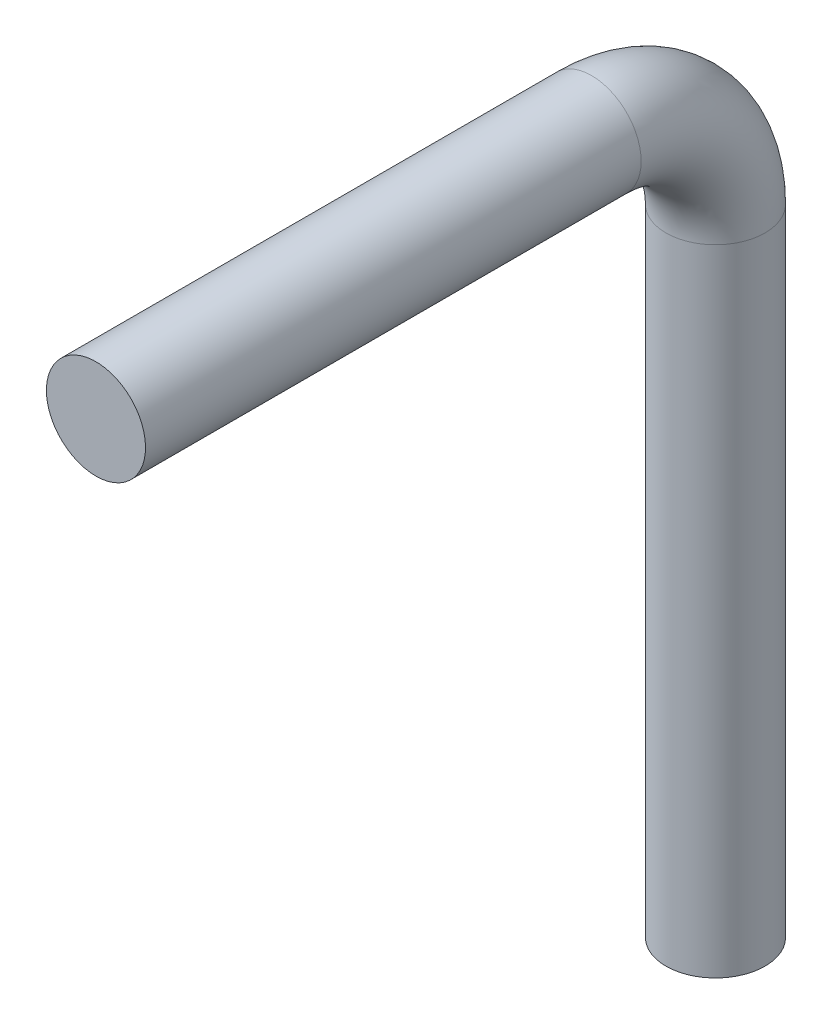
SolidWorks part; units mm, degrees
ref_plane "Front Plane" through (0, 0, 0) normal (0, 0, 1) x (1, 0, 0)
ref_plane "Top Plane" through (0, 0, 0) normal (0, 1, 0) x (1, 0, 0)
ref_plane "Right Plane" through (0, 0, 0) normal (1, 0, 0) x (0, 0, -1)
sketch "Sketch1" plane through (0, 0, 0) normal (0, 1, 0) x (1, 0, 0)
  circle A0 centre (0, 0) radius 5.08
  dimension "D1" = 10.16
sketch "Sketch2" plane through (0, 0, 0) normal (1, 0, 0) x (0, 0, -1)
  line L0 (0, 0) -> (0, 65.0875)
  line L1 (-12.7, 77.7875) -> (-63.5, 77.7875)
  arc A0 (0, 65.0875) -> (-12.7, 77.7875) centre (-12.7, 65.0875) ccw
  point P6 (0, 77.7875)
  dimension "D3" = 12.7
  dimension "D1" = 77.7875
  dimension "D2" = 63.5
sweep "Sweep1" add profiles "Sketch1" path "Sketch2"
